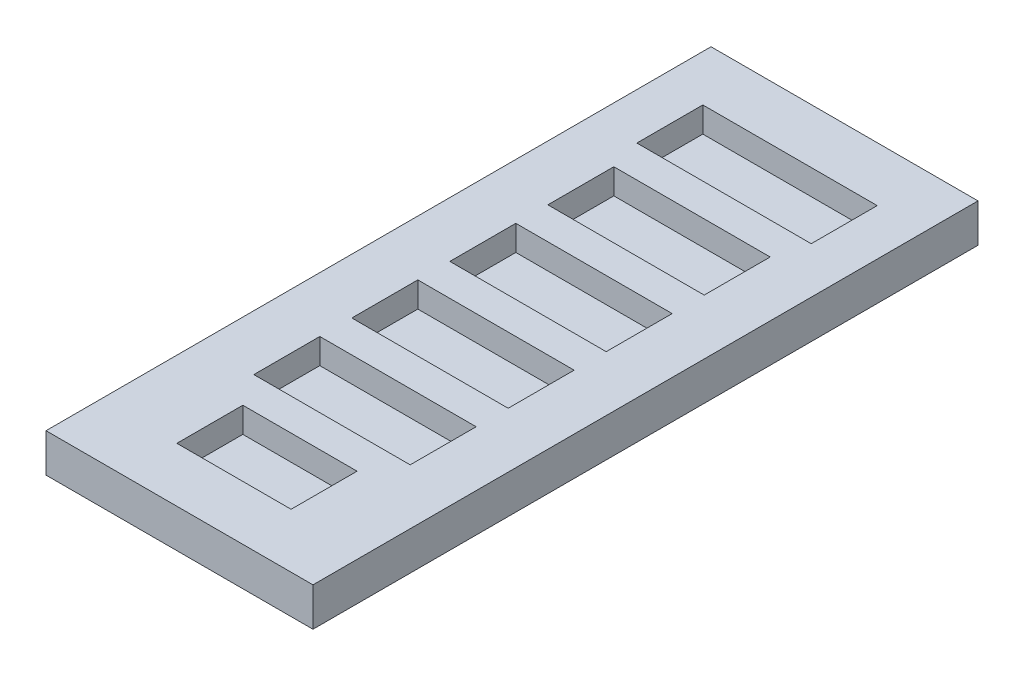
SolidWorks part; units mm, degrees
ref_plane "Спереди" through (0, 0, 0) normal (0, 0, 1) x (1, 0, 0)
ref_plane "Сверху" through (0, 0, 0) normal (0, 1, 0) x (1, 0, 0)
ref_plane "Справа" through (0, 0, 0) normal (1, 0, 0) x (0, 0, -1)
sketch "Эскиз1" plane through (0, 0, 0) normal (0, 1, 0) x (1, 0, 0)
  line L1 (0, 0) -> (0, 1106)
  line L2 (0, 0) -> (444, 0)
  line L3 (444, 0) -> (444, 1106)
  line L4 (0, 1106) -> (444, 1106)
  dimension "D1" = 444
  dimension "D2" = 1106
extrude "Наполнитель" add sketch "Эскиз1" against normal blind 64 contours L2 L1 L4 L3
sketch "Эскиз2" plane through (0, 0, 0) normal (0, 1, 0) x (1, 0, 0)
  line L0 (222, 0) -> (222, 1106) construction
  line L1 (0, 0) -> (444, 0) construction
  line L2 (0, 1106) -> (444, 1106) construction
  line L5 (222, 1015.3635) -> (77, 1015.3635)
  line L6 (77, 1015.3635) -> (77, 905.6365)
  line L7 (77, 905.6365) -> (222, 905.6365)
  line L9 (222, 852.3635) -> (92, 852.3635)
  line L10 (92, 852.3635) -> (92, 742.6365)
  line L11 (92, 742.6365) -> (222, 742.6365)
  line L13 (222, 689.3635) -> (92, 689.3635)
  line L14 (92, 689.3635) -> (92, 579.6365)
  line L15 (92, 579.6365) -> (222, 579.6365)
  line L17 (222, 526.3635) -> (92, 526.3635)
  line L18 (92, 526.3635) -> (92, 416.6365)
  line L19 (92, 416.6365) -> (222, 416.6365)
  line L21 (222, 363.3635) -> (92, 363.3635)
  line L22 (92, 363.3635) -> (92, 253.6365)
  line L23 (92, 253.6365) -> (222, 253.6365)
  line L25 (222, 200.3635) -> (127, 200.3635)
  line L26 (127, 200.3635) -> (127, 90.6365)
  line L27 (127, 90.6365) -> (222, 90.6365)
  line L30 (92, 797.5) -> (78.5, 797.5) construction
  line L31 (92, 634.5) -> (78.5, 634.5) construction
  line L33 (317, 90.6365) -> (222, 90.6365)
  line L34 (317, 200.3635) -> (317, 90.6365)
  line L35 (222, 200.3635) -> (317, 200.3635)
  line L37 (352, 253.6365) -> (222, 253.6365)
  line L38 (352, 363.3635) -> (352, 253.6365)
  line L39 (222, 363.3635) -> (352, 363.3635)
  line L41 (352, 416.6365) -> (222, 416.6365)
  line L42 (352, 526.3635) -> (352, 416.6365)
  line L43 (222, 526.3635) -> (352, 526.3635)
  line L45 (352, 579.6365) -> (222, 579.6365)
  line L46 (352, 689.3635) -> (352, 579.6365)
  line L47 (222, 689.3635) -> (352, 689.3635)
  line L49 (352, 742.6365) -> (222, 742.6365)
  line L50 (352, 852.3635) -> (352, 742.6365)
  line L51 (222, 852.3635) -> (352, 852.3635)
  line L53 (367, 905.6365) -> (222, 905.6365)
  line L54 (367, 1015.3635) -> (367, 905.6365)
  line L55 (222, 1015.3635) -> (367, 1015.3635)
  line L57 (77, 960.5) -> (63.5, 960.5) construction
  line L58 (92, 471.5) -> (78.5, 471.5) construction
  line L60 (127, 145.5) -> (113.5, 145.5) construction
  line L62 (92, 308.5) -> (78.5, 308.5) construction
  circle A1 centre (63.5, 960.5) radius 56.5 construction
  circle A2 centre (78.5, 797.5) radius 56.5 construction
  circle A3 centre (78.5, 634.5) radius 56.5 construction
  circle A4 centre (78.5, 471.5) radius 56.5 construction
  circle A5 centre (78.5, 308.5) radius 56.5 construction
  circle A6 centre (113.5, 145.5) radius 56.5 construction
  point P7 (77, 960.5)
  point P55 (0, 0)
  point P56 (0, 0)
  point P59 (0, 0)
  point P60 (0, 0)
  point P64 (0, 0)
  dimension "D4" = 113
  dimension "D12" = 113
  dimension "D18" = 113
  dimension "D23" = 113
  dimension "D24" = 113
  dimension "D25" = 113
  dimension "D2" = 163
  dimension "D3" = 145.5
  dimension "D5" = 290
  dimension "D6" = 260
  dimension "D7" = 260
  dimension "D8" = 260
  dimension "D9" = 260
  dimension "D10" = 190
  dimension "D11" = 13.5
  dimension "D13" = 163
  dimension "D14" = 13.5
  dimension "D15" = 163
  dimension "D16" = 163
  dimension "D17" = 163
  dimension "D19" = 13.5
  dimension "D20" = 13.5
  dimension "D21" = 13.5
  dimension "D22" = 13.5
  dimension "D26" = 43
  dimension "D27" = 70
extrude "Вырез-Вытянуть1" cut sketch "Эскиз2" against normal blind 42
